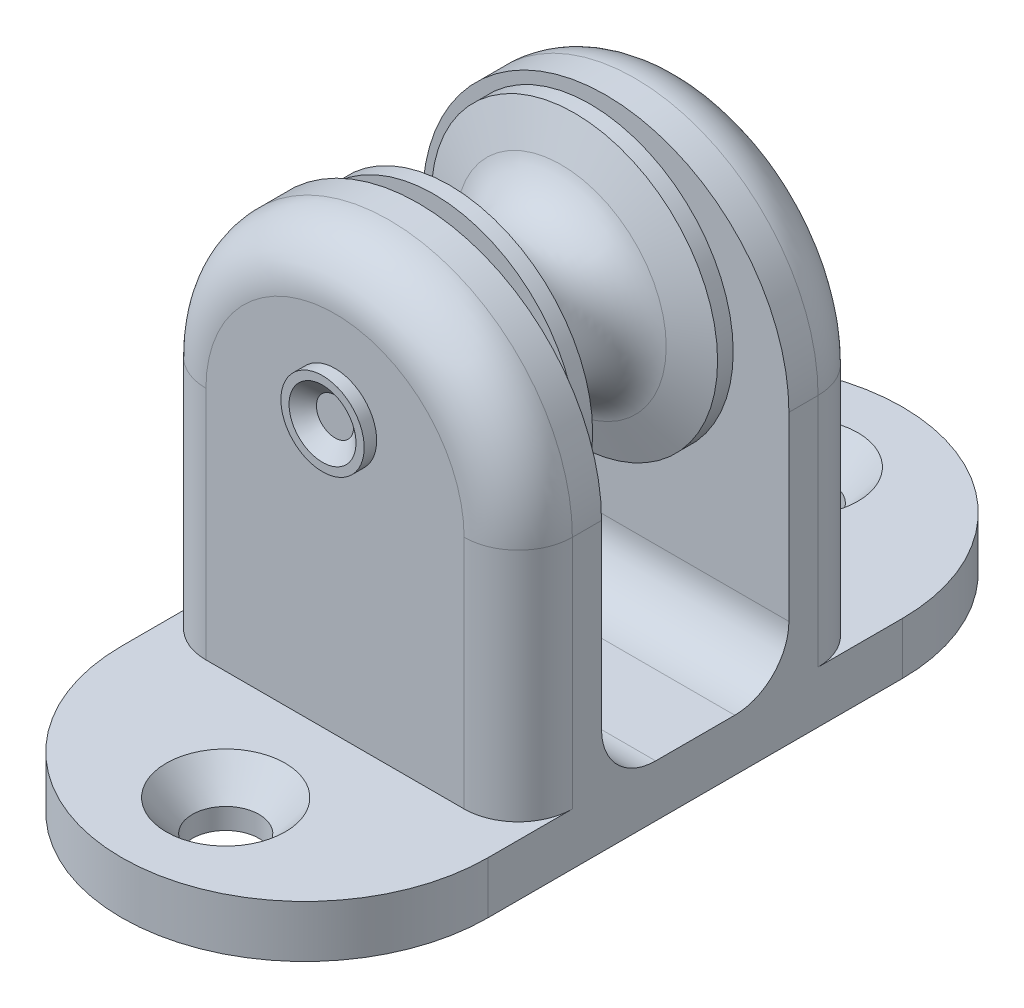
SolidWorks part; units mm, degrees
ref_plane "Front Plane" through (0, 0, 0) normal (0, 0, 1) x (1, 0, 0)
ref_plane "Top Plane" through (0, 0, 0) normal (0, 1, 0) x (1, 0, 0)
ref_plane "Right Plane" through (0, 0, 0) normal (1, 0, 0) x (0, 0, -1)
sketch "Sketch1" plane through (0, 0, 0) normal (0, 0, 1) x (1, 0, 0)
  line L0 (-11.176, -19.9707) -> (11.176, -19.9707)
  line L1 (0, 0) -> (0, -19.9707) construction
  circle A0 centre (0, 0) radius 8.7312
  point P5 (0, 8.7312)
  point P7 (0, -16.7957)
  dimension "Pulley OD" = 17.4625
  dimension "Overall Height" = 28.702
  dimension "Width" = 22.352
  dimension "Plate Height" = 3.175
ref_plane "Plane1" through (0, -19.9707, 0) normal (0, 1, 0) x (-1, 0, 0)
sketch "Sketch2" plane through (0, -19.9707, 0) normal (0, 1, 0) x (-1, 0, 0)
  line L1 (11.176, 23.8125) -> (11.176, -23.8125)
  line L2 (11.176, 23.8125) -> (-11.176, 23.8125)
  line L3 (-11.176, 23.8125) -> (-11.176, -23.8125)
  line L4 (11.176, -23.8125) -> (-11.176, -23.8125)
  line L5 (0, -17.4625) -> (0, 17.4625) construction
  circle A0 centre (0, -17.4625) radius 2.032
  circle A1 centre (0, 17.4625) radius 2.032
  dimension "Hole Dia" = 4.064
  dimension "Depth" = 47.625
  dimension "D" = 34.925
sketch "Sketch3" plane through (0, 0, 0) normal (1, 0, 0) x (0, 0, -1)
  line L0 (-4.7625, 8.7312) -> (-4.7625, 0)
  line L1 (-4.7625, 0) -> (4.7625, 0) construction
  line L2 (4.7625, 0) -> (4.7625, 8.7312)
  line L3 (4.7625, 8.7312) -> (3.81, 8.7312)
  line L4 (3.81, 8.7312) -> (2.9961, 6.4105)
  line L5 (-2.9961, 6.4105) -> (-3.81, 8.7312)
  line L6 (-3.81, 8.7312) -> (-4.7625, 8.7312)
  line L7 (-3.81, 8.7312) -> (3.81, 8.7312) construction
  line L8 (0, 0) -> (0, -19.9707) construction
  line L9 (17.4625, -19.9707) -> (-17.4625, -19.9707) construction
  line L10 (-10.795, -19.9707) -> (-10.795, 8.7312) construction
  line L11 (10.795, -19.9707) -> (10.795, 8.7312) construction
  line L12 (-4.7625, 0) -> (4.7625, 0)
  line L13 (10.795, -19.9707) -> (-10.795, -19.9707) construction
  line L14 (-4.7625, 8.7312) -> (-10.795, 8.7312) construction
  line L15 (4.7625, 8.7312) -> (10.795, 8.7312) construction
  line L16 (-5.715, 8.7312) -> (-5.715, -19.9707) construction
  line L17 (5.715, 8.7312) -> (5.715, -19.9707) construction
  line L18 (-15.4305, -19.9707) -> (15.4305, -19.9707) construction
  line L19 (-15.4305, -19.9707) -> (-19.4945, -19.9707) construction
  arc A0 (2.9961, 6.4105) -> (-2.9961, 6.4105) centre (0, 7.4612) cw
  circle A1 centre (0, 7.4612) radius 3.175 construction
  circle A2 centre (0, -7.4612) radius 3.175 construction
  dimension "Rope Dia" = 6.35
  dimension "D2" = 1.27
  dimension "D4" = 0.9525
  dimension "D5" = 14.9225
  dimension "D1" = 5.08
  dimension "D9" = 30.861
  dimension "D7" = 5.08
  dimension "D3" = 9.525
  dimension "D6" = 21.59
revolve "Revolve1" add sketch "Sketch3" angle 360 about L12
sketch "Sketch6" plane through (0, 0, 0) normal (1, 0, 0) x (0, 0, -1)
  line L0 (-10.795, 1.5875) -> (10.795, 1.5875)
  line L1 (10.795, 1.5875) -> (10.795, 3.175)
  line L2 (10.795, 3.175) -> (11.557, 3.175)
  line L3 (-10.795, 1.5875) -> (-10.795, 2.54)
  line L4 (-10.795, 2.54) -> (-11.557, 2.54)
  line L5 (-11.557, 2.54) -> (-11.557, 2.0416)
  line L6 (-10.795, 0) -> (13.081, 0) construction
  line L7 (10.795, -19.9707) -> (10.795, 8.7312) construction
  line L8 (-10.795, -19.9707) -> (-10.795, 8.7312) construction
  line L9 (-11.557, 2.0416) -> (-10.795, 1.1334)
  line L10 (-10.795, 1.1334) -> (-10.795, 0)
  line L11 (-10.795, 1.5875) -> (-11.176, 1.5875) construction
  line L12 (13.081, 0) -> (-10.795, 0)
  arc A0 (11.557, 3.175) -> (13.081, 0) centre (9.0117, 0) cw
  dimension "D1" = 3.175
  dimension "D2" = 5.08
  dimension "D3" = 6.35
  dimension "D4" = 0.762
  dimension "D5" = 2.286
  dimension "D6" = 0.762
  dimension "D7" = 50
  dimension "D8" = 0.762
revolve "Revolve2" add sketch "Sketch6" angle 360 about L12
sketch "Sketch4" plane through (0, -19.9707, 0) normal (0, 1, 0) x (-1, 0, 0)
  line L4 (11.176, -23.8125) -> (11.176, 23.8125)
  line L5 (-11.176, -23.8125) -> (11.176, -23.8125)
  line L6 (-11.176, 23.8125) -> (-11.176, -23.8125)
  line L7 (11.176, 23.8125) -> (-11.176, 23.8125)
  line L8 (11.176, -23.8125) -> (11.176, 23.8125)
  line L9 (-11.176, -23.8125) -> (11.176, -23.8125)
  line L10 (-11.176, 23.8125) -> (-11.176, -23.8125)
  line L11 (11.176, 23.8125) -> (-11.176, 23.8125)
  circle A1 centre (0, 17.4625) radius 2.032
  circle A2 centre (0, 17.4625) radius 2.032
  circle A3 centre (0, -17.4625) radius 2.032
  circle A4 centre (0, -17.4625) radius 2.032
  dimension "D1" = 0
  dimension "D2" = 0
  dimension "D3" = 0
extrude "Boss-Extrude1" add sketch "Sketch4" along normal up to vertex (3.175 mm away) separate body up to point (0, -16.7957, 0)
ref_plane "Plane2" through (0, -18.7007, 0) normal (0, -1, 0) x (1, 0, 0)
sketch "Sketch8" plane through (0, -18.7007, 0) normal (0, -1, 0) x (1, 0, 0)
  circle A0 centre (0, -17.4625) radius 2.032 construction
  circle A1 centre (0, 17.4625) radius 2.032 construction
  circle A2 centre (0, -17.4625) radius 2.032
  circle A3 centre (0, 17.4625) radius 2.032
extrude "Cut-Extrude2" cut sketch "Sketch8" against normal up to surface (1.905 mm away) draft 40
ref_plane "Plane3" through (0, 0, 10.795) normal (0, 0, 1) x (1, 0, 0)
sketch "Sketch5" plane through (0.1984, 0, 10.795) normal (0, 0, -1) x (-1, 0, 0)
  line L0 (-10.9776, -2.4448) -> (-10.9776, -16.7957)
  line L1 (-10.9776, -16.7957) -> (11.3744, -16.7957)
  line L2 (11.3744, -2.4448) -> (11.3744, -16.7957)
  line L3 (11.3744, -16.7957) -> (-10.9776, -16.7957) construction
  line L4 (11.3744, -16.7957) -> (11.3744, -19.9707) construction
  arc A0 (11.3744, -2.4448) -> (-10.9776, -2.4448) centre (0.1984, -2.4448) ccw
  circle A2 centre (0.1984, 0) radius 8.7312 construction
extrude "Boss-Extrude2" add sketch "Sketch5" along normal up to vertex (5.08 mm away) up to point (0, -19.9707, 5.715)
mirror "Mirror1" about plane through (0, 0, 0) normal (0, 0, 1) of "Boss-Extrude2"
fillet "Fillet1" radius 3.302 8 edges at (0, 8.7312, 10.795) (-11.176, -9.6202, -10.795) (11.176, -9.6203, -10.795) (0, 8.7312, -10.795) (0, -16.7957, -5.715)
sketch "Sketch7" plane through (0, 0, 0) normal (0, 1, 0) x (1, 0, 0)
  line L2 (-11.176, -23.8125) -> (11.176, -23.8125) construction
  line L3 (-11.176, -7.493) -> (-11.176, -23.8125) construction
  line L5 (-11.176, -23.8125) -> (-11.176, 23.8125) construction
  line L6 (11.176, -23.8125) -> (11.176, -7.493) construction
  line L7 (-11.176, -12.6365) -> (11.176, -12.6365) construction
  line L8 (-11.176, 12.6365) -> (-11.176, -12.6365)
  line L9 (11.176, 12.6365) -> (11.176, -12.6365)
  line L11 (0, 0) -> (-11.176, 0) construction
  arc A0 (-11.176, -12.6365) -> (11.176, -12.6365) centre (0, -12.6365) ccw
  arc A1 (-11.176, 12.6365) -> (11.176, 12.6365) centre (0, 12.6365) cw
extrude "Cut-Extrude1" cut sketch "Sketch7" against normal through all flip side to cut
sketch "Sketch9" plane through (0, 0, 0) normal (0, 1, 0) x (1, 0, 0)
  line L0 (-7.4612, 0) -> (7.4612, 0) construction
  circle A0 centre (-7.4612, 0) radius 3.175
  circle A1 centre (7.4612, 0) radius 3.175
  dimension "D2" = 6.35
  dimension "D1" = 14.9225
equation "\"D2@Sketch3\" = \"Rope Dia@Sketch3\"*.2"
equation "\"D4@Sketch3\" = \"D3@Sketch3\"/10"
equation "\"D1@Sketch9\" = \"D5@Sketch3\""
equation "\"D2@Sketch9\" = \"Rope Dia@Sketch3\""
